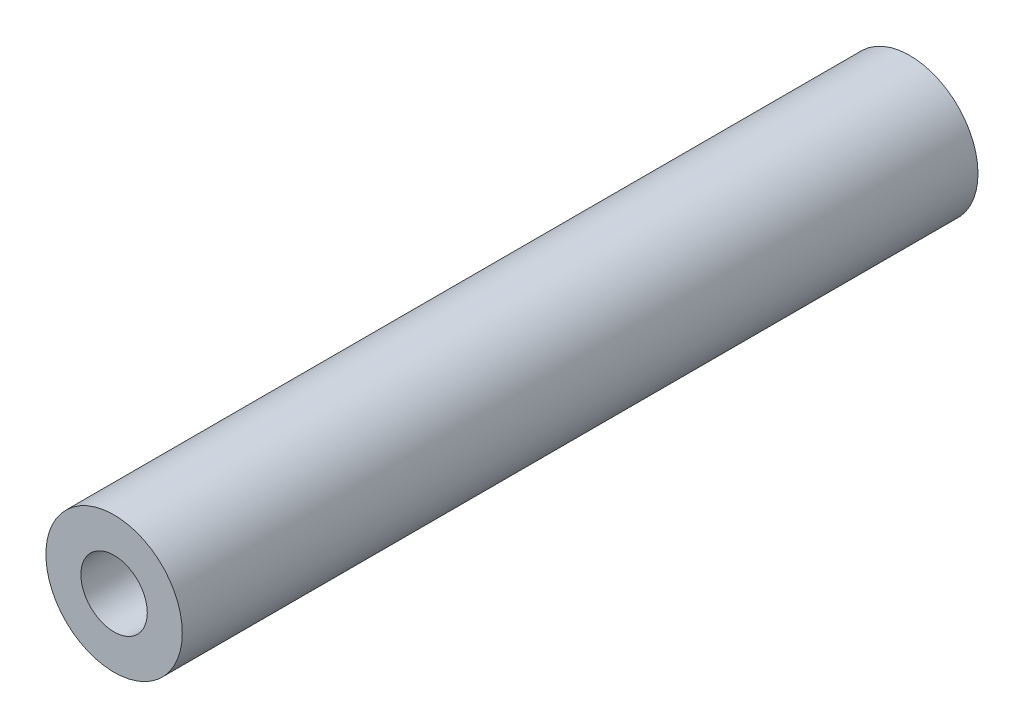
SolidWorks part; units mm, degrees
ref_plane "Front" through (0, 0, 0) normal (0, 0, 1) x (1, 0, 0)
ref_plane "Top" through (0, 0, 0) normal (0, 1, 0) x (1, 0, 0)
ref_plane "Right" through (0, 0, 0) normal (1, 0, 0) x (0, 0, -1)
sketch "Sketch1" plane through (0, 0, 0) normal (0, 0, 1) x (1, 0, 0)
  circle A0 centre (0, 0) radius 6
  dimension "D1" = 12
extrude "Boss-Extrude1" add sketch "Sketch1" along normal mid plane 70
sketch "Sketch2" plane through (0, 0, 35) normal (0, 0, 1) x (1, 0, 0)
  circle A0 centre (0, 0) radius 2.921
  dimension "D1" = 5.842
extrude "Cut-Extrude1" cut sketch "Sketch2" against normal blind 25.4
mirror "Mirror1" about plane through (0, 0, 0) normal (0, 0, 1) of "Cut-Extrude1"
fillet "Fillet1" radius 2.5 2 edges at (2.921, 0, 9.6) (2.921, 0, -9.6)
